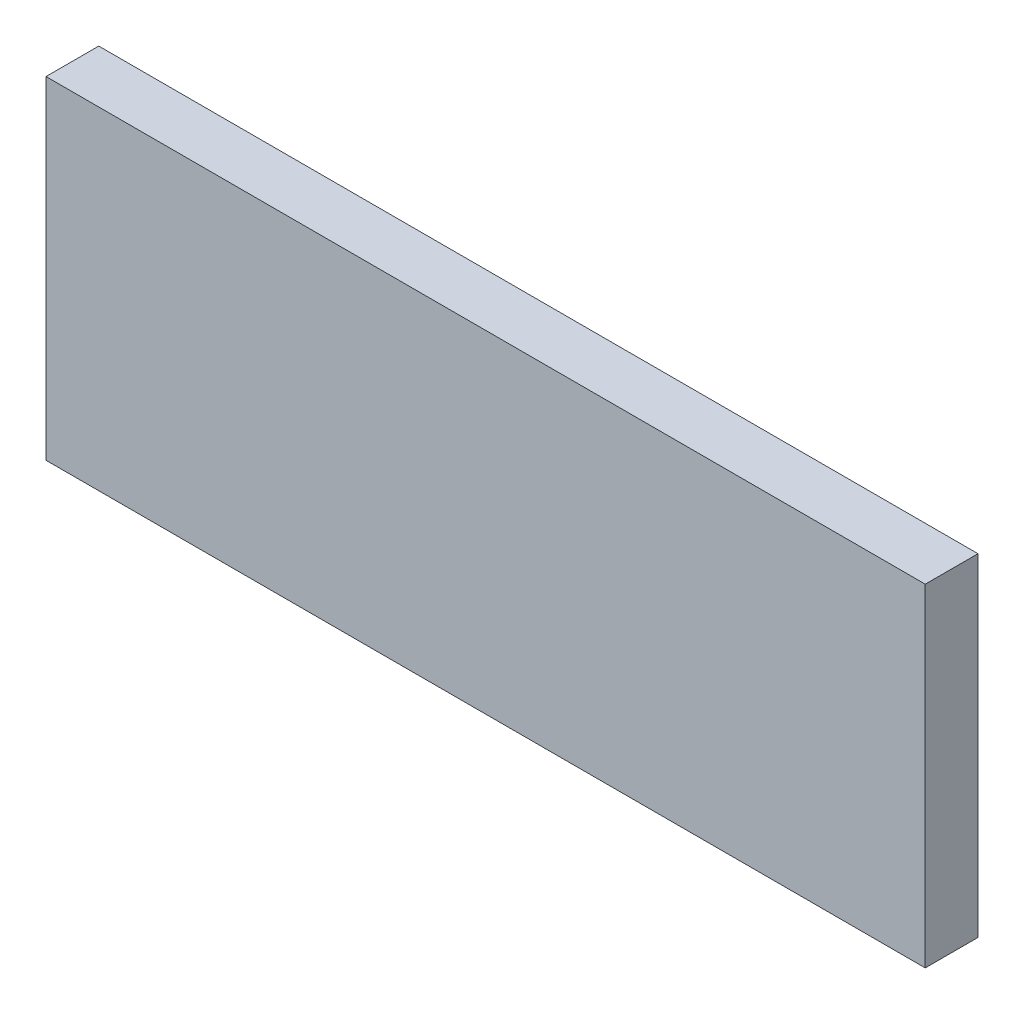
SolidWorks part; units mm, degrees
ref_plane "Front Plane" through (0, 0, 0) normal (0, 0, 1) x (1, 0, 0)
ref_plane "Top Plane" through (0, 0, 0) normal (0, 1, 0) x (1, 0, 0)
ref_plane "Right Plane" through (0, 0, 0) normal (1, 0, 0) x (0, 0, -1)
sketch "Sketch1" plane through (0, 0, 0) normal (0, 0, 1) x (1, 0, 0)
  line L1 (-25, 9.45) -> (25, 9.45)
  line L2 (-25, 9.45) -> (-25, -9.45)
  line L3 (-25, -9.45) -> (25, -9.45)
  line L4 (25, 9.45) -> (25, -9.45)
  line L5 (-25, 9.45) -> (25, -9.45) construction
  line L6 (-25, -9.45) -> (25, 9.45) construction
  point P0 (0, 0)
  dimension "D1" = 18.9
  dimension "D2" = 50
extrude "Boss-Extrude1" add sketch "Sketch1" along normal blind 3
